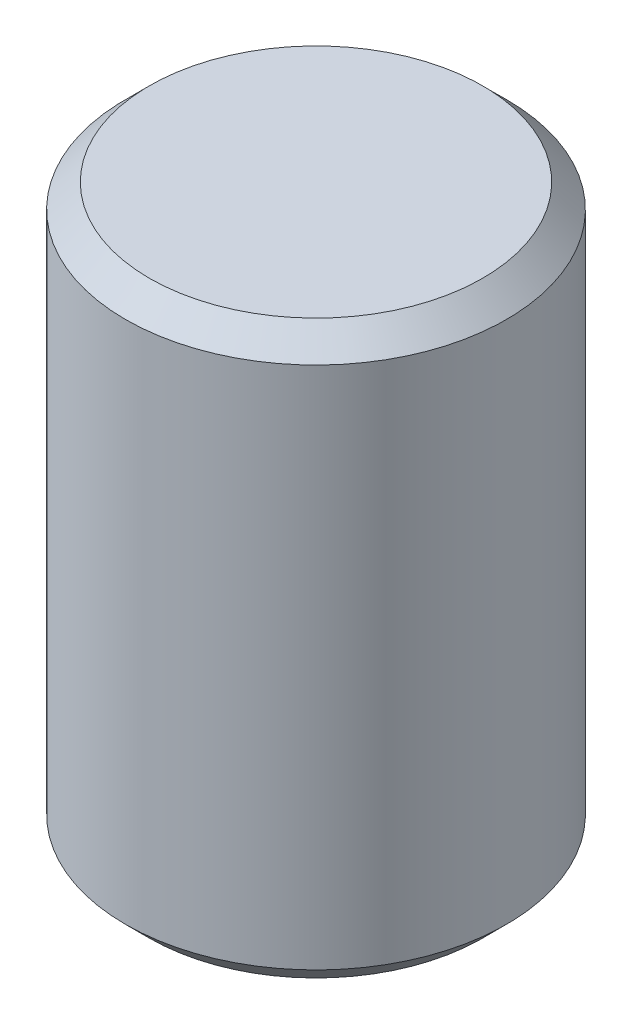
SolidWorks part; units mm, degrees
ref_plane "前视基准面" through (0, 0, 0) normal (0, 0, 1) x (1, 0, 0)
ref_plane "上视基准面" through (0, 0, 0) normal (0, 1, 0) x (1, 0, 0)
ref_plane "右视基准面" through (0, 0, 0) normal (1, 0, 0) x (0, 0, -1)
sketch "草图1" plane through (0, 0, 0) normal (0, 1, 0) x (1, 0, 0)
  circle A0 centre (0, 0) radius 4
  dimension "D1" = 8
extrude "凸台-拉伸1" add sketch "草图1" along normal blind 12
chamfer "倒角1" distance 0.5 angle 45 2 edges at (0, 0, 4) (0, 12, 4)
